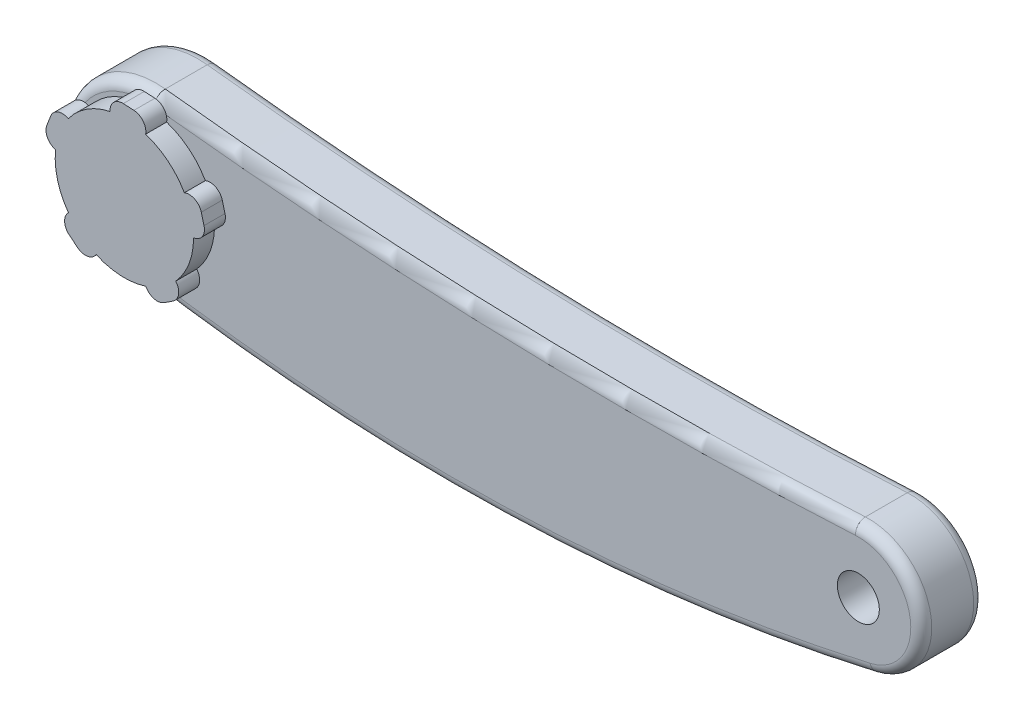
SolidWorks part; units mm, degrees
ref_plane "Front Plane" through (0, 0, 0) normal (0, 0, 1) x (1, 0, 0)
ref_plane "Top Plane" through (0, 0, 0) normal (0, 1, 0) x (1, 0, 0)
ref_plane "Right Plane" through (0, 0, 0) normal (1, 0, 0) x (0, 0, -1)
sketch "Sketch2" plane through (0, 0, 0) normal (0, 0, 1) x (1, 0, 0)
  line L0 (-66.403, 0) -> (103.597, 0) construction
  circle A0 centre (-66.403, 0) radius 20
  circle A1 centre (103.597, 0) radius 15
  arc A2 (106.9667, -14.6166) -> (-69.7649, -19.7154) centre (5.8764, 423.8817) cw
  arc A3 (-64.1496, 19.8726) -> (102.7831, 14.9779) centre (48.5235, 1013.5048) ccw
  dimension "D2" = 30
  dimension "40" = 40
  dimension "D3" = 1000
  dimension "D4" = 450
  dimension "D1" = 170
extrude "Boss-Extrude1" add sketch "Sketch2" against normal mid plane 15 contours A0 L0 A1 A3 | L0 A0 A2 A1
fillet "Fillet1" radius 2.5 8 edges at (-86.2048, 2.8087, -7.5) (-86.2048, 2.8087, 7.5) (18.8538, -25.9311, 7.5) (18.8538, -25.9311, -7.5) (118.4493, 2.0996, -7.5) (118.4493, 2.0996, 7.5) (19.2144, 13.9344, 7.5) (19.2144, 13.9344, -7.5)
sketch "Sketch3" plane through (0, 0, 7.5) normal (0, 0, 1) x (1, 0, 0)
  circle A0 centre (-66.403, 0) radius 16.5
  dimension "D1" = 33
extrude "Boss-Extrude2" add sketch "Sketch3" along normal blind 5
sketch "Sketch4" plane through (0, 0, 12.5) normal (0, 0, 1) x (1, 0, 0)
  line L0 (-66.403, 0) -> (-50.3127, 0)
  line L1 (-47.4149, 3.7765) -> (-48.0706, 6.2235)
  line L2 (-52.4684, 8.0452) -> (-66.403, 0)
  line L3 (-54.4456, -10.7665) -> (-66.403, 0)
  line L4 (-66.403, 0) -> (-61.4308, -15.3028)
  line L5 (-56.9437, -16.8918) -> (-54.8191, -15.512)
  line L6 (-72.9475, -14.6992) -> (-66.403, 0)
  line L7 (-66.403, 0) -> (-79.4204, -9.4577)
  line L8 (-79.545, -14.2161) -> (-77.5761, -15.8105)
  line L9 (-82.4052, 1.6819) -> (-66.403, 0)
  line L10 (-66.403, 0) -> (-79.4204, 9.4577)
  line L11 (-83.9845, 8.1057) -> (-84.8924, 5.7406)
  line L12 (-69.7484, 15.7387) -> (-66.403, 0)
  line L13 (-66.403, 0) -> (-61.4308, 15.3028)
  line L14 (-64.127, 19.2257) -> (-66.6569, 19.3583)
  arc A0 (-50.3127, 0) -> (-47.4149, 3.7765) centre (-50.3127, 3) ccw
  arc A1 (-48.0706, 6.2235) -> (-52.4684, 8.0452) centre (-50.9684, 5.4471) ccw
  arc A2 (-54.8191, -15.512) -> (-54.4456, -10.7665) centre (-56.453, -12.996) ccw
  arc A3 (-61.4308, -15.3028) -> (-56.9437, -16.8918) centre (-58.5777, -14.3758) ccw
  arc A4 (-77.5761, -15.8105) -> (-72.9475, -14.6992) centre (-75.6882, -13.479) ccw
  arc A5 (-79.4204, -9.4577) -> (-79.545, -14.2161) centre (-77.657, -11.8847) ccw
  arc A6 (-84.8924, 5.7406) -> (-82.4052, 1.6819) centre (-82.0916, 4.6655) ccw
  arc A7 (-79.4204, 9.4577) -> (-83.9845, 8.1057) centre (-81.1837, 7.0306) ccw
  arc A8 (-66.6569, 19.3583) -> (-69.7484, 15.7387) centre (-66.8139, 16.3624) ccw
  arc A9 (-61.4308, 15.3028) -> (-64.127, 19.2257) centre (-64.284, 16.2299) ccw
  circle A10 centre (-66.403, 0) radius 2
  point P7 (-46.403, 0)
  point P10 (-49.0825, 10)
  point P38 (-66.403, 0)
  circle M16 centre (-66.403, 0) radius 16.5
  dimension "D4" = 3
  dimension "D6" = 4
  dimension "D1" = 20
  dimension "D2" = 20
  dimension "D3" = 30
  dimension "D5" = 5
extrude "Boss-Extrude3" add sketch "Sketch4" against normal blind 5 contours A9 L14 A8 M16 | A10 L13 A9 A8 L12 M16 | A10 L0 A0 A1 L2 M16 | L1 A1 A0 M16 | A10 L4 A3 A2 L3 M16 | A3 L5 A2 M16 | A10 L7 A5 A4 L6 M16 | A5 L8 A4 M16 | A10 L10 A7 A6 L9 M16
sketch "Sketch5" plane through (0, 0, -7.5) normal (0, 0, -1) x (-1, 0, 0)
  circle A0 centre (66.403, 0) radius 5
  dimension "D1" = 10
extrude "Boss-Extrude4" add sketch "Sketch5" along normal blind 10
sketch "Sketch6" plane through (0, 0, 7.5) normal (0, 0, 1) x (1, 0, 0)
  circle A0 centre (103.597, 0) radius 5
  dimension "D1" = 10
extrude "Cut-Extrude1" cut sketch "Sketch6" against normal blind 10
